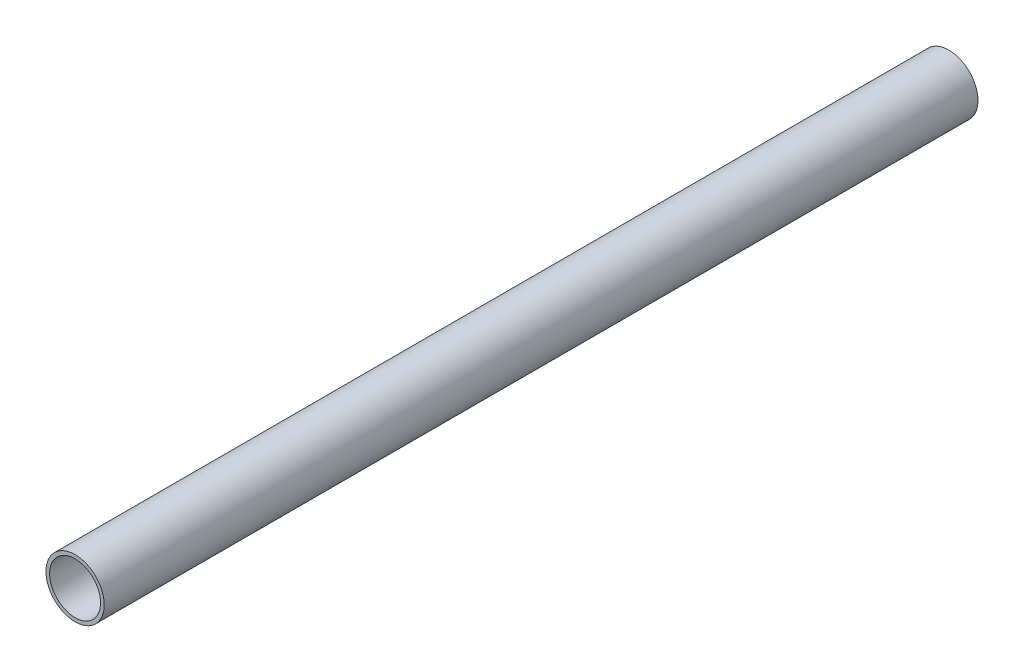
SolidWorks part; units mm, degrees
material "Thornel Mat VMA"
ref_plane "Front Plane" through (0, 0, 0) normal (0, 0, 1) x (1, 0, 0)
ref_plane "Top Plane" through (0, 0, 0) normal (0, 1, 0) x (1, 0, 0)
ref_plane "Right Plane" through (0, 0, 0) normal (1, 0, 0) x (0, 0, -1)
sketch "Sketch1" plane through (0, 0, 0) normal (0, 0, 1) x (1, 0, 0)
  circle A0 centre (0, 0) radius 7
  circle A1 centre (0, 0) radius 8
  dimension "D1" = 16
  dimension "D2" = 14
extrude "Boss-Extrude1" add sketch "Sketch1" along normal blind 240
